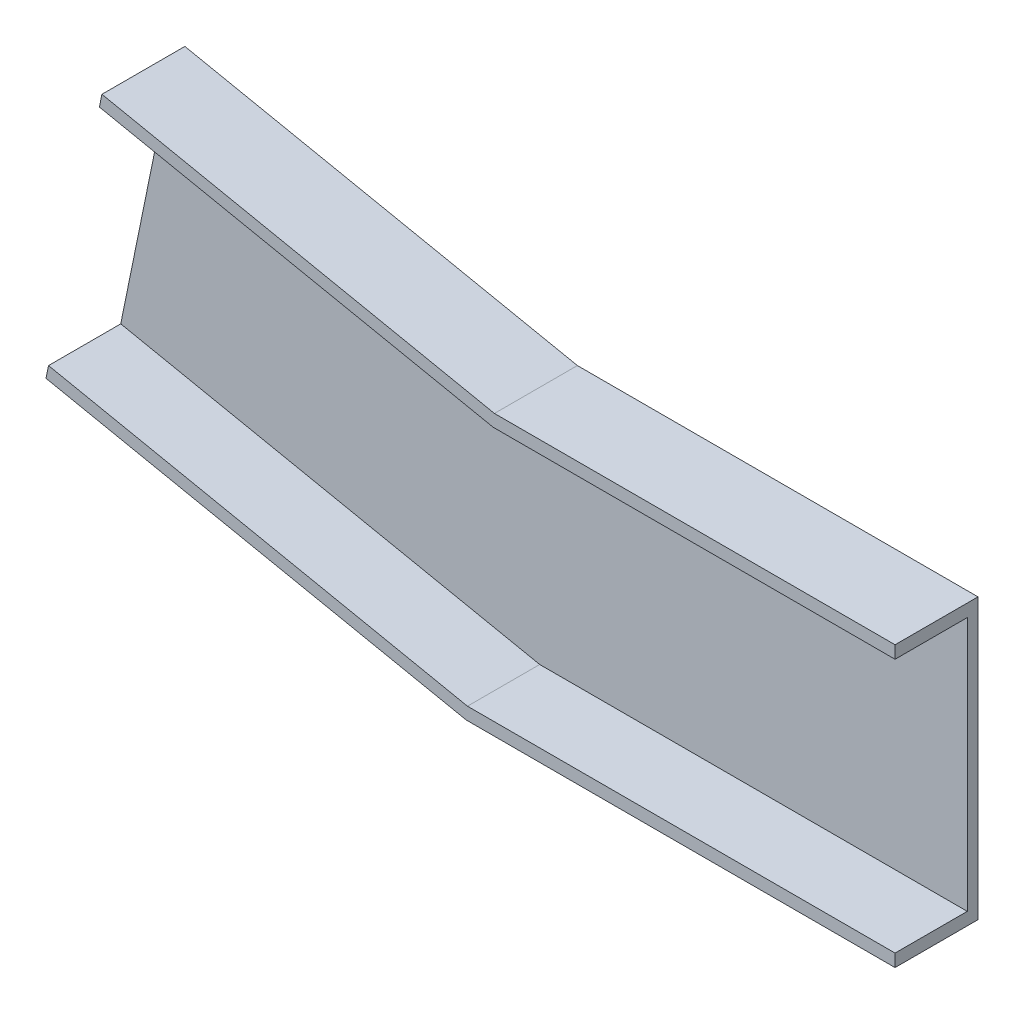
SolidWorks part; units mm, degrees
ref_plane "前视基准面" through (0, 0, 0) normal (0, 0, 1) x (1, 0, 0)
ref_plane "上视基准面" through (0, 0, 0) normal (0, 1, 0) x (1, 0, 0)
ref_plane "右视基准面" through (0, 0, 0) normal (1, 0, 0) x (0, 0, -1)
sketch "草图2" plane through (0, 0, 0) normal (0, 0, 1) x (1, 0, 0)
  line L0 (-1000, 0) -> (49000, 0) construction
  line L1 (0, 0) -> (-480, 97.9796) construction
  line L2 (-480, 97.9796) -> (-500, 0) construction
  line L3 (-500, 0) -> (0, 0) construction
  line L4 (15.1531, 150) -> (445, 150)
  line L5 (445, 150) -> (445, -150)
  line L6 (445, -150) -> (-15.1531, -150)
  line L7 (15.1531, 150) -> (-406.0092, 235.9694)
  line L8 (-406.0092, 235.9694) -> (-466.0092, -57.9694)
  line L9 (-466.0092, -57.9694) -> (-15.1531, -150)
  dimension "D1" = 100
  dimension "D2" = 500
  dimension "D3" = 300
  dimension "D4" = 445
  dimension "D5" = 300
  dimension "D6" = 445
extrude "凸台-拉伸1" add sketch "草图2" along normal blind 89
sketch "草图3" plane through (0, 0, 89) normal (0, 0, 1) x (1, 0, 0)
  line L0 (-408.7092, 222.7421) -> (13.7893, 136.5)
  line L1 (-406.0092, 235.9694) -> (-466.0092, -57.9694) construction
  line L2 (13.7893, 136.5) -> (445, 136.5)
  line L3 (445, -150) -> (445, 150) construction
  line L4 (445, 136.5) -> (445, -136.5)
  line L5 (445, -136.5) -> (-13.7893, -136.5)
  line L6 (-13.7893, -136.5) -> (-463.3092, -44.7421)
  line L7 (-463.3092, -44.7421) -> (-408.7092, 222.7421)
  line L8 (15.1531, 150) -> (-406.0092, 235.9694) construction
  line L9 (445, 150) -> (15.1531, 150) construction
  line L10 (15.1531, 150) -> (-15.1531, -150) construction
  line L11 (-466.0092, -57.9694) -> (-15.1531, -150) construction
  dimension "D1" = 13.5
  dimension "D2" = 13.5
extrude "切除-拉伸1" cut sketch "草图3" against normal blind 77.5
